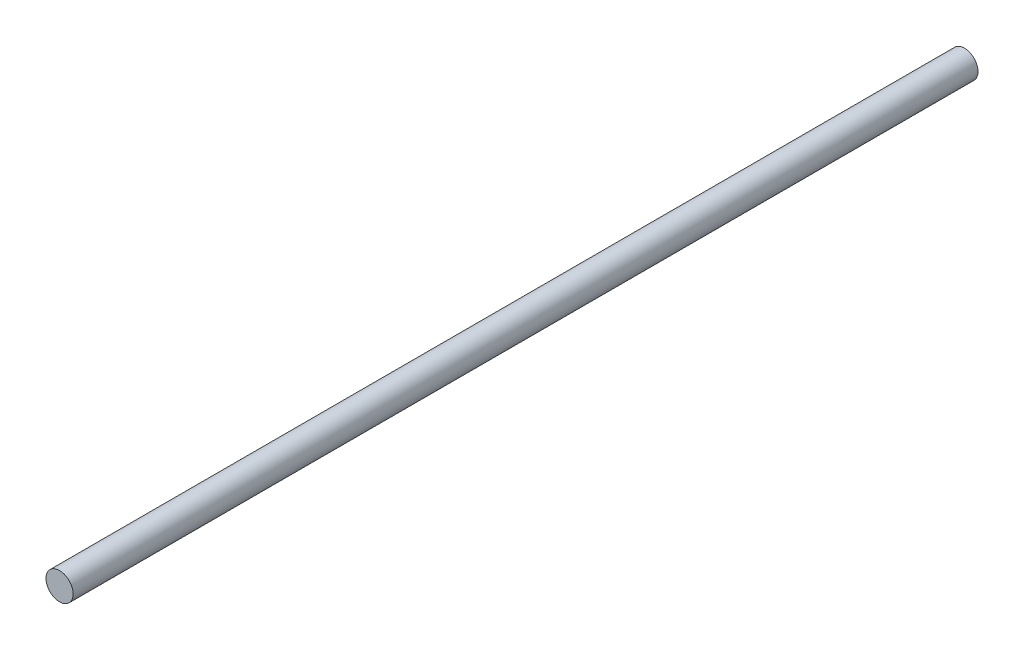
SolidWorks part; units mm, degrees
ref_plane "Top Plane" through (0, 0, 0) normal (0, 0, 1) x (1, 0, 0)
ref_plane "Front Plane" through (0, 0, 0) normal (0, 1, 0) x (1, 0, 0)
ref_plane "Right Plane" through (0, 0, 0) normal (1, 0, 0) x (0, 0, -1)
sketch "Sketch1" plane through (0, 0, 0) normal (0, 0, 1) x (1, 0, 0)
  circle A0 centre (0, 0) radius 1.5
  dimension "D1" = 3
extrude "Boss-Extrude1" add sketch "Sketch1" along normal blind 100
